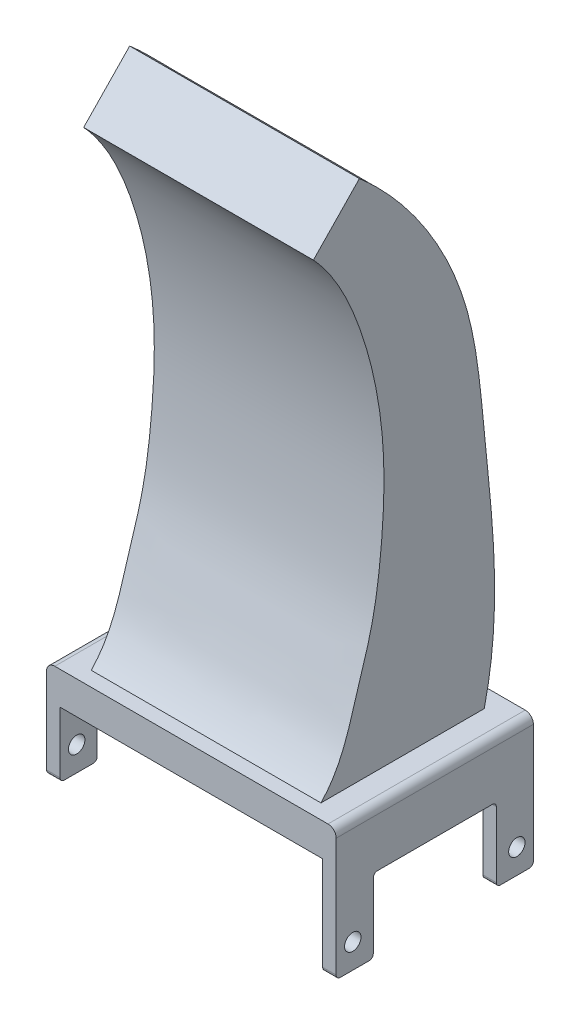
SolidWorks part; units mm, degrees
material "ABS"
ref_plane "Front Plane" through (0, 0, 0) normal (0, 0, 1) x (1, 0, 0)
ref_plane "Top Plane" through (0, 0, 0) normal (0, 1, 0) x (1, 0, 0)
ref_plane "Right Plane" through (0, 0, 0) normal (1, 0, 0) x (0, 0, -1)
sketch "Sketch1" plane through (0, 0, 0) normal (0, 1, 0) x (1, 0, 0)
  line L1 (-17.65, 12.02) -> (17.65, 12.02)
  line L2 (-17.65, 12.02) -> (-17.65, -12.02)
  line L3 (-17.65, -12.02) -> (17.65, -12.02)
  line L4 (17.65, 12.02) -> (17.65, -12.02)
  line L5 (-17.65, 12.02) -> (17.65, -12.02) construction
  line L6 (-17.65, -12.02) -> (17.65, 12.02) construction
  point P0 (0, 0)
  point P24 (0, 0)
  dimension "D1" = 35.3
  dimension "D2" = 24.04
extrude "Boss-Extrude1" add sketch "Sketch1" along normal blind 4
sketch "Sketch2" plane through (17.65, 0, 0) normal (1, 0, 0) x (0, 0, -1)
  line L0 (12.02, 4) -> (12.02, 0) construction
  line L1 (12.02, 4) -> (12.02, 0)
  line L2 (7.5, -11.95) -> (12.02, -11.95)
  line L3 (-12.02, 0) -> (12.02, 0)
  line L4 (-12.02, 0) -> (-12.02, -11.95)
  line L5 (-12.02, -11.95) -> (-7.5, -11.95)
  line L6 (12.02, 0) -> (12.02, -11.95)
  line L7 (-7.5, -2.95) -> (7.5, -2.95)
  line L8 (-7.5, -2.95) -> (-7.5, -11.95)
  line L10 (7.5, -2.95) -> (7.5, -11.95)
  line L11 (0, 16.4113) -> (0, -19.9375) construction
  circle A0 centre (10, -8.95) radius 1
  circle A1 centre (-10, -8.95) radius 1
  point P5 (0, -11.95)
  line M10 (-12.02, 0) -> (12.02, 0)
  dimension "D4" = 2
  dimension "D1" = 11.95
  dimension "D2" = 9
  dimension "D3" = 15
  dimension "D5" = 2.5
  dimension "D6" = 7.5
  dimension "D7" = 3
extrude "Boss-Extrude2" add sketch "Sketch2" against normal blind 1.65 contours L11 L4 L5 L8 L7 A1 M10 | L3 L11 L7 L10 L2 L6 A0
sketch "Sketch3" plane through (-17.65, 0, 0) normal (-1, 0, 0) x (0, 0, 1)
  line L0 (12.02, 4) -> (12.02, 0) construction
  line L1 (12.02, 4) -> (12.02, 0)
  line L2 (7.5, -7.95) -> (12.02, -7.95)
  line L3 (-12.02, 0) -> (12.02, 0)
  line L4 (-12.02, 0) -> (-12.02, -7.95)
  line L5 (-12.02, -7.95) -> (-7.5, -7.95)
  line L6 (12.02, 0) -> (12.02, -7.95)
  line L7 (-7.5, -2.95) -> (7.5, -2.95)
  line L8 (-7.5, -2.95) -> (-7.5, -7.95)
  line L10 (7.5, -2.95) -> (7.5, -7.95)
  line L11 (0, 3.5412) -> (0, -14.6742) construction
  circle A0 centre (10, -4.95) radius 1
  circle A1 centre (-10, -4.95) radius 1
  point P5 (0, -9.26)
  line M12 (-12.02, 0) -> (12.02, 0)
  dimension "D4" = 2
  dimension "D1" = 7.95
  dimension "D2" = 15
  dimension "D3" = 5
  dimension "D5" = 2.5
  dimension "D6" = 7.5
  dimension "D7" = 3
extrude "Boss-Extrude3" add sketch "Sketch3" against normal blind 1.65 contours L11 L4 L5 L8 L7 A1 M12 | L3 L11 L7 L10 L2 L6 A0
fillet "Fillet1" radius 1 1 edges at (17.65, 4, 0)
fillet "Fillet2" radius 1 1 edges at (-17.65, 4, 0)
fillet "Fillet3" radius 0.5 12 edges at (-16.825, -7.95, 12.02) (-16.825, -7.95, 7.5) (-16.825, -2.95, 7.5) (-16.825, -2.95, -7.5) (-16.825, -7.95, -7.5) (-16.825, -7.95, -12.02) (16.825, -11.95, -12.02) (16.825, -11.95, -7.5) (16.825, -2.95, -7.5) (16.825, -2.95, 7.5) (16.825, -11.95, 7.5) (16.825, -11.95, 12.02)
sketch "Sketch4" plane through (0, 0, 0) normal (1, 0, 0) x (0, 0, -1)
  line L0 (-12.02, 4) -> (12.02, 4) construction
  line L1 (9.6737, 4) -> (-10.2265, 4)
  line L2 (-5.5441, 67.5563) -> (-11.1514, 61.7623)
  spline S0 degree 3 poles (9.6737, 4) (11.9611, 13.6453) (10.0233, 27.979) (8.1881, 50.6655) (0.6673, 62.1813) (-5.5441, 67.5563) knots 0 0 0 0 0.431185 0.63431 1 1 1 1
  spline S1 degree 3 poles (-10.2265, 4) (-7.7964, 6.5096) (-6.3361, 12.0864) (-3.7801, 19.7839) (-2.7776, 27.3757) (-2.3321, 35.5339) (-3.2048, 43.9235) (-5.6017, 52.9561) (-8.5405, 58.9234) (-11.1514, 61.7623) knots 0 0 0 0 0.167475 0.276326 0.399787 0.541879 0.677544 0.812359 1 1 1 1
extrude "Boss-Extrude4" add sketch "Sketch4" along normal blind 14 and the other way blind 14 contours S0 L2 S1 L1
